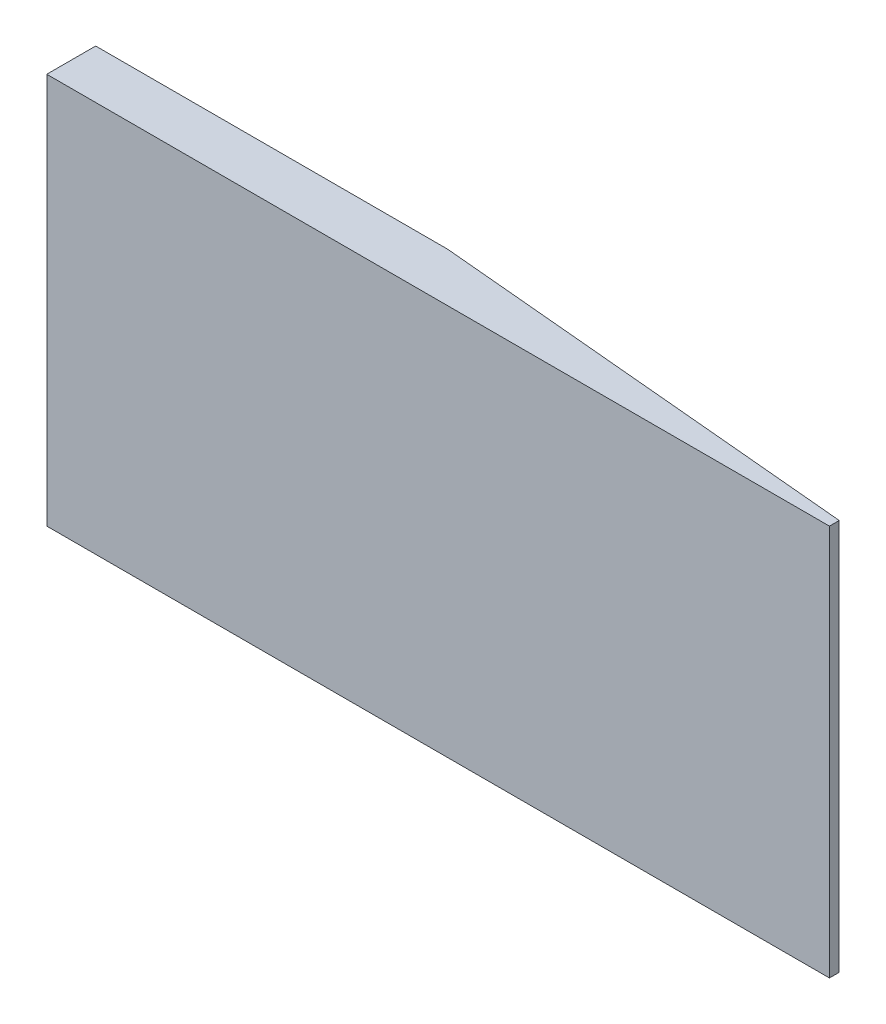
SolidWorks part; units mm, degrees
ref_plane "Front Plane" through (0, 0, 0) normal (0, 0, 1) x (1, 0, 0)
ref_plane "Top Plane" through (0, 0, 0) normal (0, 1, 0) x (1, 0, 0)
ref_plane "Right Plane" through (0, 0, 0) normal (1, 0, 0) x (0, 0, -1)
sketch "Sketch2" plane through (0, 0, 0) normal (0, 0, 1) x (1, 0, 0)
  line L0 (194.7047, 6.35) -> (194.7047, -3.175) construction
  line L1 (184.15, 6.35) -> (215.9, 6.35) construction
  line L2 (215.9, -3.175) -> (184.15, -3.175) construction
  line L3 (194.7047, 6.35) -> (194.7047, 1.5875) construction
  line L4 (194.7047, 6.35) -> (194.7047, 14.2875) construction
  line L7 (194.7047, 14.2875) -> (245.5047, 14.2875)
  line L8 (194.7047, 14.2875) -> (194.7047, -11.1125)
  line L9 (194.7047, -11.1125) -> (245.5047, -11.1125)
  line L10 (245.5047, 14.2875) -> (245.5047, -11.1125)
  dimension "D1" = 7.9375
  dimension "D2" = 25.4
  dimension "D3" = 50.8
extrude "Boss-Extrude1" add sketch "Sketch2" along normal blind 3.175
chamfer "Chamfer1" distance 27.94 distance2 2.54 1 edges at (245.5047, 1.5875, 0)
